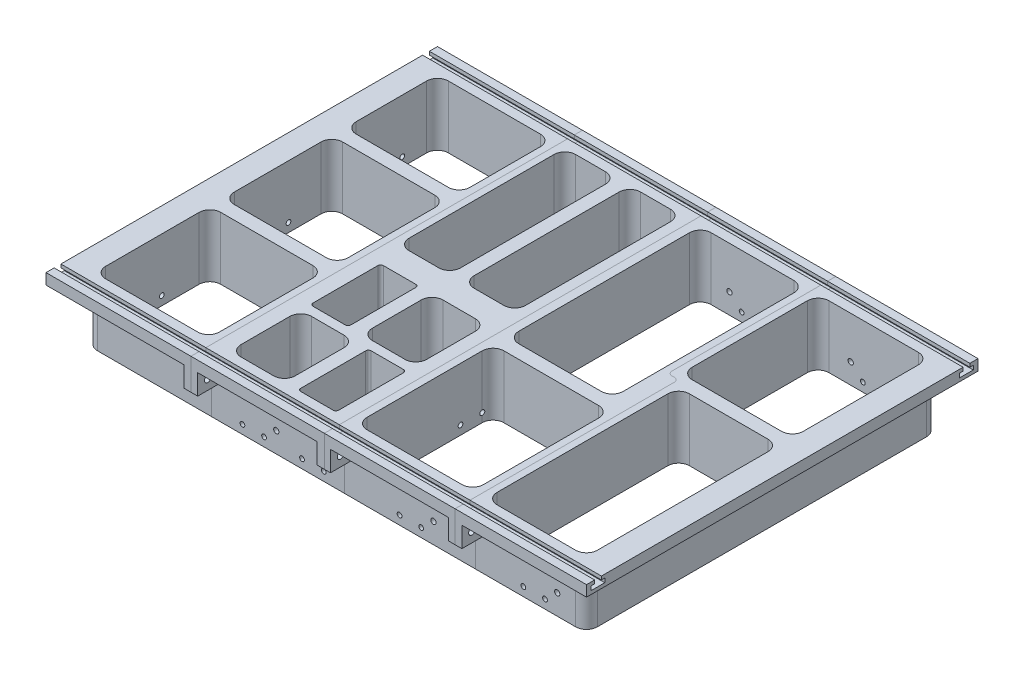
SolidWorks part; units mm, degrees
ref_plane "Front Plane" through (0, 0, 0) normal (0, 0, 1) x (1, 0, 0)
ref_plane "Top Plane" through (0, 0, 0) normal (0, 1, 0) x (1, 0, 0)
ref_plane "Right Plane" through (0, 0, 0) normal (1, 0, 0) x (0, 0, -1)
sketch "Sketch1" plane through (0, 0, 0) normal (0, 1, 0) x (1, 0, 0)
  line L1 (199.5, -144.5) -> (-199.5, -144.5)
  line L2 (199.5, -144.5) -> (199.5, 144.5)
  line L3 (199.5, 144.5) -> (-199.5, 144.5)
  line L4 (-199.5, -144.5) -> (-199.5, 144.5)
  line L5 (199.5, -144.5) -> (-199.5, 144.5) construction
  line L6 (199.5, 144.5) -> (-199.5, -144.5) construction
  point P0 (0, 0)
  dimension "D1" = 399
  dimension "D2" = 289
extrude "Boss-Extrude1" add sketch "Sketch1" along normal blind 53
sketch "Sketch3" plane through (0, 0, 0) normal (0, -1, 0) x (-1, 0, 0)
  line L23 (184.5, -129.5) -> (184.5, 129.5)
  line L24 (184.5, 129.5) -> (-184.5, 129.5)
  line L25 (-184.5, 129.5) -> (-184.5, -129.5)
  line L26 (-184.5, -129.5) -> (184.5, -129.5)
  line L27 (184.5, -129.5) -> (184.5, 129.5)
  line L28 (184.5, 129.5) -> (-184.5, 129.5)
  line L29 (-184.5, 129.5) -> (-184.5, -129.5)
  line L30 (-184.5, -129.5) -> (184.5, -129.5)
  dimension "D1" = 15
extrude "Cut-Extrude2" cut sketch "Sketch3" against normal blind 45 flip side to cut
sketch "Sketch2" plane through (0, 53, 0) normal (0, 1, 0) x (1, 0, 0)
  line L1 (-173.5, -126.5) -> (-105.5, -126.5)
  line L2 (-181.5, -118.5) -> (-181.5, -49.5)
  line L3 (-173.5, -41.5) -> (-105.5, -41.5)
  line L4 (-97.5, -118.5) -> (-97.5, -49.5)
  line L5 (-173.5, -31.5) -> (-105.5, -31.5)
  line L6 (-181.5, -23.5) -> (-181.5, 40.5)
  line L7 (-173.5, 48.5) -> (-105.5, 48.5)
  line L8 (-181.5, 126.5) -> (-181.5, -126.5)
  line L9 (-181.5, -126.5) -> (181.5, -126.5)
  line L10 (181.5, -126.5) -> (181.5, 126.5)
  line L11 (181.5, 126.5) -> (-181.5, 126.5)
  line L12 (-181.5, 126.5) -> (-181.5, -126.5) construction
  line L13 (-181.5, -126.5) -> (181.5, -126.5) construction
  line L14 (181.5, -126.5) -> (181.5, 126.5) construction
  line L15 (181.5, 126.5) -> (-181.5, 126.5) construction
  line L16 (-97.5, -23.5) -> (-97.5, 40.5)
  line L17 (-173.5, 126.5) -> (-105.5, 126.5)
  line L18 (-181.5, 118.5) -> (-181.5, 66.5)
  line L19 (-173.5, 58.5) -> (-105.5, 58.5)
  line L20 (-97.5, 118.5) -> (-97.5, 66.5)
  line L21 (173.5, -126.5) -> (115.5, -126.5)
  line L22 (181.5, -118.5) -> (181.5, 7.5)
  line L23 (173.5, 15.5) -> (115.5, 15.5)
  line L24 (107.5, -118.5) -> (107.5, 7.5)
  line L25 (173.5, 126.5) -> (107.5, 126.5)
  line L26 (181.5, 118.5) -> (181.5, 33.5)
  line L27 (173.5, 25.5) -> (107.5, 25.5)
  line L28 (99.5, 118.5) -> (99.5, 33.5)
  line L29 (81.5, 126.5) -> (20.5, 126.5)
  line L30 (89.5, 118.5) -> (89.5, -7.5)
  line L31 (81.5, -15.5) -> (20.5, -15.5)
  line L32 (12.5, 118.5) -> (12.5, -7.5)
  line L33 (-9.5, 126.5) -> (-31.5, 126.5)
  line L34 (-1.5, 118.5) -> (-1.5, 11.5)
  line L35 (-9.5, 3.5) -> (-31.5, 3.5)
  line L36 (-39.5, 118.5) -> (-39.5, 11.5)
  line L37 (-57.5, 126.5) -> (-79.5, 126.5)
  line L38 (-49.5, 118.5) -> (-49.5, 11.5)
  line L39 (-57.5, 3.5) -> (-79.5, 3.5)
  line L40 (-87.5, 118.5) -> (-87.5, 11.5)
  line L41 (-79.5, -15.5) -> (-55.5, -15.5)
  line L42 (-81.5, -17.5) -> (-81.5, -65.5)
  line L43 (-79.5, -67.5) -> (-55.5, -67.5)
  line L44 (-53.5, -17.5) -> (-53.5, -65.5)
  line L45 (-73.5, -126.5) -> (-49.5, -126.5)
  line L46 (-81.5, -118.5) -> (-81.5, -82.5)
  line L47 (-73.5, -74.5) -> (-49.5, -74.5)
  line L48 (-41.5, -118.5) -> (-41.5, -82.5)
  line L49 (-35.5, -15.5) -> (-11.5, -15.5)
  line L50 (-43.5, -23.5) -> (-43.5, -59.5)
  line L51 (-35.5, -67.5) -> (-11.5, -67.5)
  line L52 (-3.5, -23.5) -> (-3.5, -59.5)
  line L53 (-29.5, -74.5) -> (-5.5, -74.5)
  line L54 (-31.5, -76.5) -> (-31.5, -124.5)
  line L55 (-29.5, -126.5) -> (-5.5, -126.5)
  line L56 (-3.5, -76.5) -> (-3.5, -124.5)
  line L57 (89.5, -126.5) -> (19.5, -126.5)
  line L58 (97.5, -118.5) -> (97.5, -33.5)
  line L59 (89.5, -25.5) -> (19.5, -25.5)
  line L60 (11.5, -118.5) -> (11.5, -33.5)
  arc A0 (-79.5, 126.5) -> (-87.5, 118.5) centre (-79.5, 118.5) ccw
  arc A1 (-79.5, 3.5) -> (-87.5, 11.5) centre (-79.5, 11.5) cw
  arc A2 (-49.5, 11.5) -> (-57.5, 3.5) centre (-57.5, 11.5) cw
  arc A3 (-57.5, 126.5) -> (-49.5, 118.5) centre (-57.5, 118.5) cw
  arc A4 (-31.5, 126.5) -> (-39.5, 118.5) centre (-31.5, 118.5) ccw
  arc A5 (-31.5, 3.5) -> (-39.5, 11.5) centre (-31.5, 11.5) cw
  arc A6 (-1.5, 11.5) -> (-9.5, 3.5) centre (-9.5, 11.5) cw
  arc A7 (-9.5, 126.5) -> (-1.5, 118.5) centre (-9.5, 118.5) cw
  arc A8 (20.5, 126.5) -> (12.5, 118.5) centre (20.5, 118.5) ccw
  arc A9 (20.5, -15.5) -> (12.5, -7.5) centre (20.5, -7.5) cw
  arc A10 (89.5, -7.5) -> (81.5, -15.5) centre (81.5, -7.5) cw
  arc A11 (81.5, 126.5) -> (89.5, 118.5) centre (81.5, 118.5) cw
  arc A12 (107.5, 126.5) -> (99.5, 118.5) centre (107.5, 118.5) ccw
  arc A13 (173.5, 126.5) -> (181.5, 118.5) centre (173.5, 118.5) cw
  arc A14 (181.5, 33.5) -> (173.5, 25.5) centre (173.5, 33.5) cw
  arc A15 (107.5, 25.5) -> (99.5, 33.5) centre (107.5, 33.5) cw
  arc A16 (115.5, 15.5) -> (107.5, 7.5) centre (115.5, 7.5) ccw
  arc A17 (181.5, 7.5) -> (173.5, 15.5) centre (173.5, 7.5) ccw
  arc A18 (173.5, -126.5) -> (181.5, -118.5) centre (173.5, -118.5) ccw
  arc A19 (115.5, -126.5) -> (107.5, -118.5) centre (115.5, -118.5) cw
  arc A20 (89.5, -126.5) -> (97.5, -118.5) centre (89.5, -118.5) ccw
  arc A21 (97.5, -33.5) -> (89.5, -25.5) centre (89.5, -33.5) ccw
  arc A22 (19.5, -25.5) -> (11.5, -33.5) centre (19.5, -33.5) ccw
  arc A23 (19.5, -126.5) -> (11.5, -118.5) centre (19.5, -118.5) cw
  arc A28 (-43.5, -59.5) -> (-35.5, -67.5) centre (-35.5, -59.5) ccw
  arc A29 (-11.5, -67.5) -> (-3.5, -59.5) centre (-11.5, -59.5) ccw
  arc A30 (-11.5, -15.5) -> (-3.5, -23.5) centre (-11.5, -23.5) cw
  arc A31 (-35.5, -15.5) -> (-43.5, -23.5) centre (-35.5, -23.5) ccw
  arc A36 (-49.5, -74.5) -> (-41.5, -82.5) centre (-49.5, -82.5) cw
  arc A37 (-49.5, -126.5) -> (-41.5, -118.5) centre (-49.5, -118.5) ccw
  arc A38 (-73.5, -126.5) -> (-81.5, -118.5) centre (-73.5, -118.5) cw
  arc A39 (-81.5, -82.5) -> (-73.5, -74.5) centre (-73.5, -82.5) cw
  arc A40 (-105.5, -41.5) -> (-97.5, -49.5) centre (-105.5, -49.5) cw
  arc A41 (-105.5, -126.5) -> (-97.5, -118.5) centre (-105.5, -118.5) ccw
  arc A42 (-173.5, -126.5) -> (-181.5, -118.5) centre (-173.5, -118.5) cw
  arc A43 (-181.5, -49.5) -> (-173.5, -41.5) centre (-173.5, -49.5) cw
  arc A44 (-105.5, 48.5) -> (-97.5, 40.5) centre (-105.5, 40.5) cw
  arc A45 (-105.5, -31.5) -> (-97.5, -23.5) centre (-105.5, -23.5) ccw
  arc A46 (-173.5, -31.5) -> (-181.5, -23.5) centre (-173.5, -23.5) cw
  arc A47 (-181.5, 40.5) -> (-173.5, 48.5) centre (-173.5, 40.5) cw
  arc A48 (-105.5, 126.5) -> (-97.5, 118.5) centre (-105.5, 118.5) cw
  arc A49 (-105.5, 58.5) -> (-97.5, 66.5) centre (-105.5, 66.5) ccw
  arc A50 (-181.5, 66.5) -> (-173.5, 58.5) centre (-173.5, 66.5) ccw
  arc A51 (-173.5, 126.5) -> (-181.5, 118.5) centre (-173.5, 118.5) ccw
  arc A52 (-81.5, -17.5) -> (-79.5, -15.5) centre (-79.5, -17.5) cw
  arc A53 (-79.5, -67.5) -> (-81.5, -65.5) centre (-79.5, -65.5) cw
  arc A54 (-53.5, -65.5) -> (-55.5, -67.5) centre (-55.5, -65.5) cw
  arc A55 (-55.5, -15.5) -> (-53.5, -17.5) centre (-55.5, -17.5) cw
  arc A56 (-3.5, -76.5) -> (-5.5, -74.5) centre (-5.5, -76.5) ccw
  arc A57 (-5.5, -126.5) -> (-3.5, -124.5) centre (-5.5, -124.5) ccw
  arc A58 (-31.5, -124.5) -> (-29.5, -126.5) centre (-29.5, -124.5) ccw
  arc A59 (-31.5, -76.5) -> (-29.5, -74.5) centre (-29.5, -76.5) cw
  point P54 (-87.5, 126.5)
  point P57 (-87.5, 3.5)
  point P62 (-49.5, 126.5)
  point P65 (-39.5, 126.5)
  point P72 (-1.5, 126.5)
  point P75 (12.5, 126.5)
  point P82 (89.5, 126.5)
  point P85 (99.5, 126.5)
  point P91 (181.5, 25.5)
  point P103 (107.5, -126.5)
  point P106 (97.5, -126.5)
  point P109 (97.5, -25.5)
  point P114 (11.5, -126.5)
  point P119 (-3.5, -126.5)
  point P122 (-31.5, -126.5)
  point P127 (-43.5, -67.5)
  point P130 (-3.5, -67.5)
  point P139 (-81.5, -15.5)
  point P142 (-81.5, -67.5)
  point P149 (-41.5, -126.5)
  point P152 (-81.5, -126.5)
  point P155 (-81.5, -74.5)
  point P171 (-181.5, -31.5)
  point P174 (-181.5, 48.5)
  point P177 (-97.5, 126.5)
  point P182 (-181.5, 58.5)
  point P188 (-81.5, -15.5)
  point P191 (-81.5, -67.5)
  point P200 (-3.5, -126.5)
  point P203 (-31.5, -126.5)
  dimension "D31" = 8
  dimension "D32" = 8
  dimension "D33" = 8
  dimension "D34" = 2
  dimension "D35" = 2
  dimension "D2" = 74
  dimension "D3" = 82
  dimension "D4" = 101
  dimension "D5" = 10
  dimension "D6" = 86
  dimension "D7" = 10
  dimension "D8" = 15
  dimension "D9" = 28
  dimension "D10" = 40
  dimension "D11" = 52
  dimension "D12" = 52
  dimension "D13" = 77
  dimension "D14" = 38
  dimension "D15" = 38
  dimension "D16" = 84
  dimension "D17" = 68
  dimension "D18" = 80
  dimension "D19" = 10
  dimension "D20" = 10
  dimension "D21" = 7
  dimension "D22" = 10
  dimension "D23" = 101
  dimension "D24" = 10
  dimension "D25" = 10
  dimension "D26" = 123
  dimension "D27" = 10
  dimension "D28" = 10
  dimension "D29" = 40
  dimension "D30" = 10
  dimension "D1" = 18
extrude "Mini bin cuts" cut sketch "Sketch2" against normal blind 46
fillet "Fillet1" radius 8 4 edges at (-184.5, 22.5, -129.5) (184.5, 22.5, -129.5) (184.5, 22.5, 129.5) (-184.5, 22.5, 129.5)
sketch "Sketch6" plane through (-184.5, 0, 0) normal (-1, 0, 0) x (0, 0, 1)
  line L0 (129.5, 45) -> (129.5, 0) construction
  line L1 (-129.5, 0) -> (129.5, 0)
  line L2 (-129.5, 0) -> (-129.5, 7)
  line L3 (-129.5, 7) -> (129.5, 7)
  line L4 (129.5, 0) -> (129.5, 7)
  dimension "D1" = 7
extrude "Cut-Extrude5" cut sketch "Sketch6" against normal through all
sketch "Sketch7" plane through (-184.5, 0, 0) normal (-1, 0, 0) x (0, 0, 1)
  line L0 (-121.5, 13.5) -> (121.5, 13.5) construction
  line L1 (-121.5, 45) -> (-121.5, 7) construction
  line L2 (121.5, 7) -> (121.5, 45) construction
  line L3 (121.5, 7) -> (-121.5, 7) construction
  line L4 (-92.5, 13.5) -> (-92.5, 45) construction
  line L5 (121.5, 45) -> (-121.5, 45) construction
  line L6 (-8.5, 13.5) -> (-8.5, 45) construction
  line L7 (85, 13.5) -> (85, 45) construction
  circle A0 centre (-100.5, 13.5) radius 1.75
  circle A1 centre (-84.5, 13.5) radius 1.75
  circle A2 centre (-16.5, 13.5) radius 1.75
  circle A3 centre (77, 13.5) radius 1.75
  circle A4 centre (-0.5, 13.5) radius 1.75
  circle A5 centre (93, 13.5) radius 1.75
  circle A6 centre (-75.5, 21.963) radius 1.95
  circle A7 centre (102, 21.963) radius 1.95
  circle A8 centre (8.5, 21.963) radius 1.95
  dimension "D2" = 36.5
  dimension "D5" = 3.5
  dimension "D7" = 3.5
  dimension "D9" = 3.5
  dimension "D11" = 3.9
  dimension "D12" = 3.9
  dimension "D13" = 3.9
  dimension "D1" = 6.5
  dimension "D3" = 29
  dimension "D4" = 113
  dimension "D6" = 8
  dimension "D8" = 8
  dimension "D10" = 8
  dimension "D14" = 17
  dimension "D15" = 17
  dimension "D16" = 17
  dimension "D17" = 8.463
  dimension "D18" = 8.463
  dimension "D19" = 8.463
extrude "Holes Lids 1,2,3" cut sketch "Sketch7" against normal up to surface (3 mm away) up to face at (-181.5, 30, 84)
sketch "Sketch8" plane through (0, 0, 129.5) normal (0, 0, 1) x (1, 0, 0)
  line L0 (-176.5, 13.5) -> (176.5, 13.5) construction
  line L1 (-176.5, 45) -> (-176.5, 7) construction
  line L2 (176.5, 7) -> (176.5, 45) construction
  line L5 (-61.5, 45) -> (-61.5, 7) construction
  line L6 (176.5, 45) -> (-176.5, 45) construction
  line L7 (176.5, 7) -> (-176.5, 7) construction
  line L8 (-17.5, 45) -> (-17.5, 7) construction
  line L11 (145.896, 45) -> (145.896, 7) construction
  line L12 (54.5, 45) -> (54.5, 7) construction
  circle A0 centre (-69.5, 13.5) radius 1.75
  circle A1 centre (-25.5, 13.5) radius 1.75
  circle A2 centre (46.5, 13.5) radius 1.75
  circle A3 centre (137.896, 13.5) radius 1.75
  circle A4 centre (153.896, 13.5) radius 1.75
  circle A5 centre (62.5, 13.5) radius 1.75
  circle A6 centre (-9.5, 13.5) radius 1.75
  circle A7 centre (-53.5, 13.5) radius 1.75
  circle A8 centre (-44.5, 21.96) radius 1.95
  circle A9 centre (-0.5, 21.96) radius 1.95
  circle A10 centre (71.5, 21.96) radius 1.95
  circle A11 centre (162.896, 21.96) radius 1.95
  dimension "D5" = 3.5
  dimension "D6" = 3.5
  dimension "D7" = 3.5
  dimension "D8" = 3.5
  dimension "D14" = 3.9
  dimension "D16" = 8.46
  dimension "D17" = 17
  dimension "D18" = 8.46
  dimension "D19" = 17
  dimension "D20" = 8.46
  dimension "D22" = 8.46
  dimension "D1" = 115
  dimension "D2" = 159
  dimension "D3" = 6.5
  dimension "D4" = 122
  dimension "D9" = 8
  dimension "D10" = 8
  dimension "D11" = 8
  dimension "D12" = 8
  dimension "D13" = 30.604
  dimension "D15" = 17
  dimension "D21" = 17
extrude "Holes Lids 8,9,12,13" cut sketch "Sketch8" against normal up to surface (3 mm away) up to face at (54.5, 30, 126.5)
sketch "Sketch9" plane through (0, 0, -129.5) normal (0, 0, -1) x (-1, 0, 0)
  line L0 (-176.5, 13.5) -> (176.5, 13.5) construction
  line L1 (-176.5, 45) -> (-176.5, 7) construction
  line L2 (176.5, 7) -> (176.5, 45) construction
  line L3 (-140.5, 45) -> (-140.5, 7) construction
  line L4 (176.5, 45) -> (-176.5, 45) construction
  line L5 (-176.5, 7) -> (176.5, 7) construction
  line L7 (20.5, 45) -> (20.5, 7) construction
  line L8 (199.5, 45) -> (-199.5, 45) construction
  line L9 (68.5, 45) -> (68.5, 7) construction
  line L10 (-51, 45) -> (-51, 7) construction
  circle A0 centre (-148.5, 13.5) radius 1.75
  circle A1 centre (-59, 13.5) radius 1.75
  circle A2 centre (12.5, 13.5) radius 1.75
  circle A3 centre (60.5, 13.5) radius 1.75
  circle A4 centre (-132.5, 13.5) radius 1.75
  circle A5 centre (-43, 13.5) radius 1.75
  circle A6 centre (28.5, 13.5) radius 1.75
  circle A7 centre (76.5, 13.5) radius 1.75
  circle A8 centre (-123.5, 21.96) radius 1.95
  circle A9 centre (-34, 21.96) radius 1.95
  circle A10 centre (37.5, 21.96) radius 1.95
  circle A11 centre (85.5, 21.96) radius 1.95
  dimension "D6" = 3.5
  dimension "D10" = 8
  dimension "D11" = 3.5
  dimension "D12" = 3.5
  dimension "D13" = 3.5
  dimension "D14" = 3.9
  dimension "D15" = 3.9
  dimension "D16" = 3.9
  dimension "D17" = 17
  dimension "D19" = 17
  dimension "D20" = 8.46
  dimension "D21" = 8.46
  dimension "D22" = 8.46
  dimension "D23" = 8.46
  dimension "D24" = 3.9
  dimension "D25" = 17
  dimension "D1" = 6.5
  dimension "D2" = 36
  dimension "D3" = 125.5
  dimension "D4" = 197
  dimension "D5" = 245
  dimension "D7" = 8
  dimension "D8" = 8
  dimension "D9" = 8
  dimension "D18" = 17
extrude "Holes Lids 4,5,10,11" cut sketch "Sketch9" against normal up to surface (3 mm away) up to face at (51, 30, -126.5)
sketch "Sketch11" plane through (-3.5, 0, 0) normal (-1, 0, 0) x (0, 0, 1)
  line L0 (23.5, 13.5) -> (59.5, 13.5) construction
  line L1 (23.5, 7) -> (23.5, 53) construction
  line L2 (59.5, 7) -> (59.5, 53) construction
  line L3 (41.5, 7) -> (41.5, 53) construction
  line L4 (59.5, 7) -> (23.5, 7) construction
  line L5 (23.5, 53) -> (59.5, 53) construction
  circle A0 centre (33.5, 13.5) radius 1.75
  circle A1 centre (49.5, 13.5) radius 1.75
  dimension "D2" = 3.5
  dimension "D1" = 6.5
  dimension "D3" = 8
extrude "Hole Lid 7" cut sketch "Sketch11" against normal up to next
sketch "Sketch12" plane through (-81.5, 0, 0) normal (1, 0, 0) x (0, 0, -1)
  line L0 (-65.5, 13.5) -> (-17.5, 13.5) construction
  line L1 (-65.5, 7) -> (-65.5, 53) construction
  line L2 (-17.5, 7) -> (-17.5, 53) construction
  line L3 (-41.5, 7) -> (-41.5, 53) construction
  line L5 (-17.5, 7) -> (-65.5, 7) construction
  line L6 (-17.5, 53) -> (-65.5, 53) construction
  circle A0 centre (-49.5, 13.5) radius 1.75
  circle A1 centre (-33.5, 13.5) radius 1.75
  dimension "D2" = 3.5
  dimension "D1" = 6.5
  dimension "D3" = 8
extrude "Hole Lid 6" cut sketch "Sketch12" against normal blind 15
sketch "Sketch13" plane through (0, 7, 0) normal (0, -1, 0) x (1, 0, 0)
  line L0 (-81.5, 17.5) -> (-81.5, 65.5) construction
  line L1 (-173.5, 41.5) -> (-105.5, 41.5) construction
  line L2 (-81.5, 25.43) -> (-88.5, 25.43) construction
  line L4 (81.5, 15.5) -> (20.5, 15.5) construction
  line L5 (11.5, 38.905) -> (-3.5, 38.905) construction
  line L6 (11.5, 118.5) -> (11.5, 33.5) construction
  line L7 (-3.5, 23.5) -> (-3.5, 59.5) construction
  circle A0 centre (-88.5, 45.5) radius 1.95
  circle A2 centre (3.5, 18.84) radius 1.95
  circle A3 centre (3.5, 58.97) radius 1.95
  circle A4 centre (-88.5, 5.36) radius 1.95
  dimension "D1" = 3.9
  dimension "D3" = 4
  dimension "D5" = 3.9
  dimension "D8" = 7
  dimension "D2" = 7
  dimension "D4" = 20.07
  dimension "D6" = 3.34
  dimension "D7" = 20.065
extrude "Servo brackets 6,7," cut sketch "Sketch13" against normal blind 15
sketch "Sketch14" plane through (-199.5, 0, 0) normal (-1, 0, 0) x (0, 0, 1)
  line L0 (133.5, 53) -> (133.5, 50.5)
  line L2 (133.5, 50.5) -> (131, 50.5)
  line L3 (131, 50.5) -> (131, 47.5)
  line L4 (131, 47.5) -> (141, 47.5)
  line L5 (141, 47.5) -> (141, 50.5)
  line L6 (141, 50.5) -> (138.5, 50.5)
  line L7 (138.5, 50.5) -> (138.5, 53)
  line L8 (138.5, 53) -> (133.5, 53)
  line L9 (144.5, 53) -> (144.5, 45) construction
  line L10 (0, 0) -> (0, 45) construction
  line L11 (144.5, 45) -> (-144.5, 45) construction
  line L12 (-138.5, 53) -> (-133.5, 53)
  line L13 (-138.5, 50.5) -> (-138.5, 53)
  line L14 (-141, 50.5) -> (-138.5, 50.5)
  line L15 (-141, 47.5) -> (-141, 50.5)
  line L16 (-131, 47.5) -> (-141, 47.5)
  line L17 (-131, 50.5) -> (-131, 47.5)
  line L18 (-133.5, 50.5) -> (-131, 50.5)
  line L19 (-133.5, 53) -> (-133.5, 50.5)
  line L20 (-144.5, 53) -> (144.5, 53) construction
  point P7 (136, 47.5)
  dimension "D1" = 10
  dimension "D2" = 5
  dimension "D3" = 3
  dimension "D4" = 2.5
  dimension "D5" = 2.5
  dimension "D6" = 8.5
extrude "Structural Cuts" cut sketch "Sketch14" against normal through all
sketch "Sketch16" plane through (0, 0, 129.5) normal (0, 0, 1) x (1, 0, 0)
  line L5 (176.5, 45) -> (-176.5, 45) construction
  line L6 (-184.5, 7) -> (-184.5, 45) construction
  line L7 (0.5, 45) -> (10.5, 45)
  line L8 (0.5, 45) -> (0.5, 30)
  line L9 (0.5, 30) -> (10.5, 30)
  line L10 (10.5, 45) -> (10.5, 30)
  line L11 (97.5, 45) -> (107.5, 45)
  line L12 (97.5, 45) -> (97.5, 30)
  line L13 (97.5, 30) -> (107.5, 30)
  line L14 (107.5, 45) -> (107.5, 30)
  line L15 (-97.5, 45) -> (-87.5, 45)
  line L16 (-97.5, 45) -> (-97.5, 30)
  line L17 (-97.5, 30) -> (-87.5, 30)
  line L18 (-87.5, 45) -> (-87.5, 30)
  dimension "D1" = 87
  dimension "D2" = 10
  dimension "D3" = 185
  dimension "D4" = 10
  dimension "D5" = 282
  dimension "D6" = 10
  dimension "D7" = 15
  dimension "D8" = 15
  dimension "D9" = 15
extrude "First Set of Bolts" add sketch "Sketch16" along normal up to surface (15 mm away) up to face at (0, 49, 144.5)
sketch "Sketch17" plane through (0, 0, -129.5) normal (0, 0, -1) x (-1, 0, 0)
  line L0 (176.5, 45) -> (-176.5, 45) construction
  line L1 (-107.5, 45) -> (-97.5, 45)
  line L2 (-107.5, 45) -> (-107.5, 30)
  line L3 (-107.5, 30) -> (-97.5, 30)
  line L4 (-97.5, 45) -> (-97.5, 30)
  line L5 (184.5, 45) -> (184.5, 7) construction
  line L6 (-10.5, 45) -> (-0.5, 45)
  line L7 (-10.5, 45) -> (-10.5, 30)
  line L8 (-10.5, 30) -> (-0.5, 30)
  line L9 (-0.5, 45) -> (-0.5, 30)
  line L10 (87.5, 45) -> (97.5, 45)
  line L11 (87.5, 45) -> (87.5, 30)
  line L12 (87.5, 30) -> (97.5, 30)
  line L13 (97.5, 45) -> (97.5, 30)
  dimension "D1" = 15
  dimension "D2" = 10
  dimension "D3" = 10
  dimension "D4" = 10
  dimension "D5" = 87
  dimension "D6" = 185
  dimension "D7" = 282
extrude "Second Set of Bolts" add sketch "Sketch17" along normal up to surface (15 mm away) up to face at (0, 49, -144.5)
sketch "Sketch18" plane through (-184.5, 0, 0) normal (-1, 0, 0) x (0, 0, 1)
  line L0 (0, 7) -> (0, 45) construction
  line L1 (121.5, 7) -> (-121.5, 7) construction
  line L2 (144.5, 45) -> (-144.5, 45) construction
  line L4 (144.5, 30) -> (144.5, 45) construction
  circle A0 centre (137, 37.5) radius 2.5
  circle A1 centre (-137, 37.5) radius 2.5
  point P12 (144.5, 37.5)
  dimension "D1" = 5
  dimension "D2" = 7.5
extrude "Cut-Extrude6" cut sketch "Sketch18" against normal through all
chamfer "Chamfer2" distance 2 angle 45 6 edges at (-97.5, 37.5, -139.5) (0.5, 37.5, -139.5) (97.5, 37.5, -139.5) (97.5, 37.5, 134.5) (0.5, 40, 137) (-97.5, 40, 137)
sketch "Split Lines" plane through (0, 53, 0) normal (0, 1, 0) x (1, 0, 0)
  line L0 (-92.5, 144.5) -> (-92.5, -144.5)
  line L1 (199.5, 144.5) -> (-199.5, 144.5) construction
  line L2 (-199.5, -144.5) -> (199.5, -144.5) construction
  line L3 (6, 144.5) -> (6, -144.5)
  line L4 (94.5, 144.5) -> (94.5, 23.5)
  line L5 (97.5, 20.5) -> (99.5, 20.5)
  line L6 (102.5, 17.5) -> (102.5, -144.5)
  line L7 (-87.5, 118.5) -> (-87.5, 11.5) construction
  line L8 (12.5, 118.5) -> (12.5, -7.5) construction
  line L9 (99.5, 118.5) -> (99.5, 33.5) construction
  line L10 (107.5, -118.5) -> (107.5, 7.5) construction
  line L11 (173.5, 25.5) -> (107.5, 25.5) construction
  arc A0 (99.5, 20.5) -> (102.5, 17.5) centre (99.5, 17.5) cw
  arc A1 (94.5, 23.5) -> (97.5, 20.5) centre (97.5, 23.5) ccw
  dimension "D6" = 3
  dimension "D1" = 5
  dimension "D2" = 6.5
  dimension "D3" = 5
  dimension "D4" = 5
  dimension "D5" = 5
split "Split1" trim tools "Split Lines" bodies to split 160 resulting bodies 161 162 163 164
